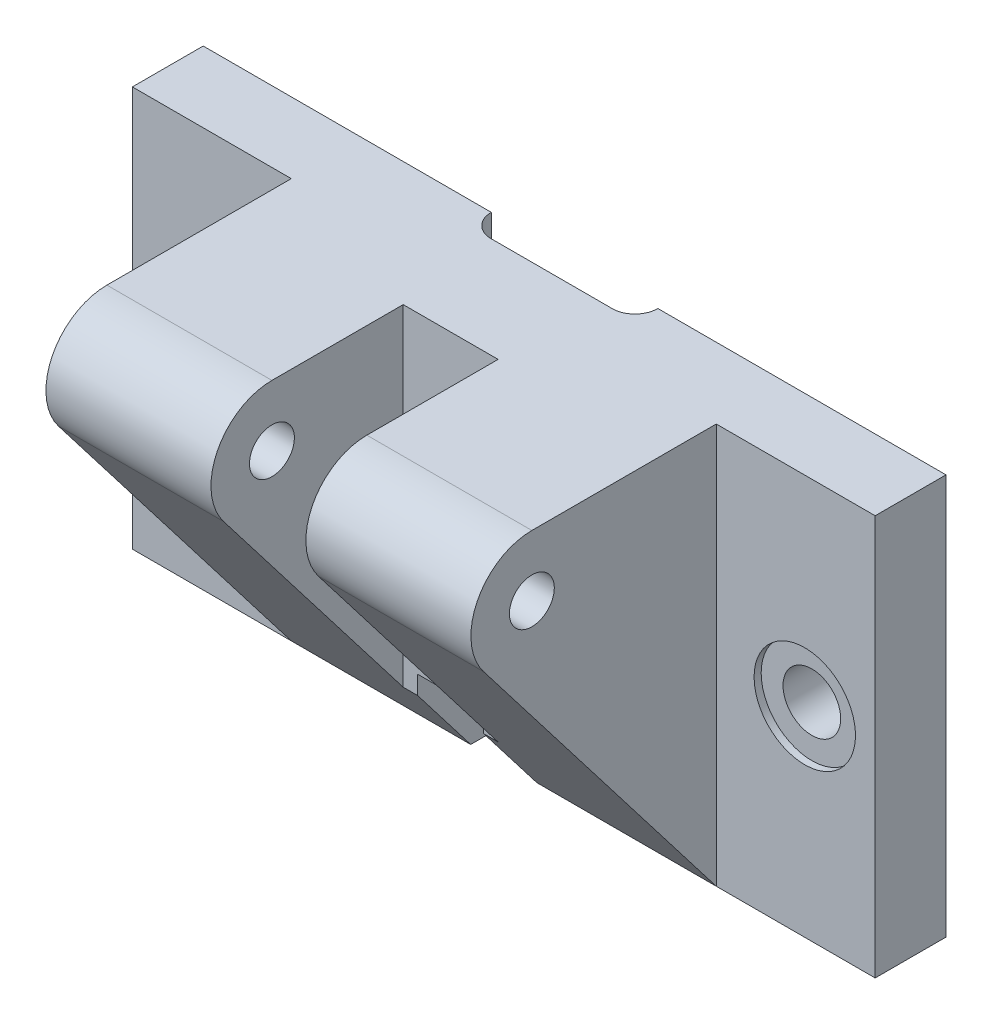
SolidWorks part; units mm, degrees
ref_plane "Płaszczyzna przednia" through (0, 0, 0) normal (0, 0, 1) x (1, 0, 0)
ref_plane "Płaszczyzna górna" through (0, 0, 0) normal (0, 1, 0) x (1, 0, 0)
ref_plane "Płaszczyzna prawa" through (0, 0, 0) normal (1, 0, 0) x (0, 0, -1)
sketch "Szkic1" plane through (0, 0, 0) normal (0, 0, 1) x (1, 0, 0)
  line L0 (0, 89.3165) -> (0, -100.7451) construction
  line L2 (0, 62.9812) -> (-104.8721, 62.9812)
  line L3 (0, 62.9812) -> (0, -50.062)
  line L4 (0, -50.062) -> (-104.8721, -50.062)
  line L5 (-104.8721, 62.9812) -> (-104.8721, -50.062)
  circle A0 centre (-84.9964, 6.4596) radius 8.1392
extrude "Dodanie-wyciągnięcie1" add sketch "Szkic1" along normal blind 20
ref_plane "Płaszczyzna1" through (0, 0, 20) normal (0, 0, 1) x (1, 0, 0)
sketch "Szkic2" plane through (0, 0, 20) normal (0, 0, 1) x (1, 0, 0)
  circle A0 centre (-84.9964, 6.4596) radius 14.3159
extrude "Wytnij-wyciągnięcie1" cut sketch "Szkic2" against normal blind 2 contours A0
mirror "Lustro2" about plane through (0, 62.9812, 20) normal (-1, 0, 0) of "Wytnij-wyciągnięcie1", "Dodanie-wyciągnięcie1"
ref_plane "Płaszczyzna2" through (0, 62.9812, 0) normal (0, 1, 0) x (1, 0, 0)
sketch "Szkic6" plane through (0, 62.9812, 0) normal (0, 1, 0) x (1, 0, 0)
  line L0 (-104.8721, -6.4678) -> (104.8721, -6.4678) construction
  line L1 (104.8721, -20) -> (104.8721, 0) construction
  line L2 (-104.8721, -20) -> (-104.8721, 0) construction
  line L3 (0, -6.4678) -> (0, -20) construction
  line L4 (-62.1737, -20) -> (62.1737, -20) construction
  line L5 (0, -20) -> (0, 0) construction
  line L6 (-23.533, 0) -> (23.533, 0)
  line L7 (104.8721, 0) -> (-104.8721, 0) construction
  line L8 (-16.4916, -6.4678) -> (16.4916, -6.4678)
  arc A0 (-23.533, 0) -> (-16.4916, -6.4678) centre (-17.0419, 0) ccw
  arc A1 (23.533, 0) -> (16.4916, -6.4678) centre (17.0419, 0) cw
  point P16 (0, 0)
extrude "Wytnij-wyciągnięcie2" cut sketch "Szkic6" against normal blind 140
sketch "Szkic9" plane through (0, 0, 0) normal (1, 0, 0) x (0, 0, -1)
  line L0 (-20, 62.9812) -> (-72.0689, 62.9812)
  line L1 (11, 62.9812) -> (-11, 62.9812) construction
  line L2 (-85.7036, 35.2757) -> (-20, -50.062)
  line L3 (-20, 62.1737) -> (-20, -62.1737) construction
  line L4 (-20, 62.9812) -> (-20, -50.062)
  arc A0 (-72.0689, 62.9812) -> (-85.7036, 35.2757) centre (-72.0689, 45.7734) ccw
  circle A1 centre (-72.0689, 45.7734) radius 6.341
extrude "Dodanie-wyciągnięcie2" add sketch "Szkic9" along normal blind 60
mirror "Lustro3" about plane through (0, 45.7734, 72.0689) normal (1, 0, 0) of "Dodanie-wyciągnięcie2"
ref_plane "Płaszczyzna3" through (0, 0, 35) normal (0, 0, 1) x (1, 0, 0)
sketch "Szkic12" plane through (0, 0, 35) normal (0, 0, 1) x (1, 0, 0)
  line L0 (0, 62.9812) -> (0, -50.062) construction
  line L1 (39.6379, 62.9812) -> (-39.6379, 62.9812) construction
  line L2 (60, -50.062) -> (-60, -50.062) construction
  line L3 (-13.4008, 62.9812) -> (13.4008, 62.9812)
  line L4 (13.4008, 62.9812) -> (13.4008, -50.062)
  line L5 (13.4008, -50.062) -> (-13.4008, -50.062)
  line L6 (-13.4008, -50.062) -> (-13.4008, 62.9812)
  point P10 (0, 0)
  point P11 (0, -50.062)
  point P12 (-13.4008, -50.062)
extrude "Wytnij-wyciągnięcie8" cut sketch "Szkic12" along normal blind 99
sketch "Szkic13" plane through (0, 0, 35) normal (0, 0, 1) x (1, 0, 0)
  line L0 (0, -25.3643) -> (0, -68.6154) construction
  line L1 (9.3383, -68.6154) -> (-9.3383, -68.6154)
  line L2 (9.3383, -68.6154) -> (9.3383, -25.3643)
  line L3 (9.3383, -25.3643) -> (-9.3383, -25.3643)
  line L4 (-9.3383, -68.6154) -> (-9.3383, -25.3643)
  line L5 (13.4008, -30.5795) -> (-13.4008, -30.5795) construction
  point P8 (0, -30.5795)
extrude "Wytnij-wyciągnięcie9" cut sketch "Szkic13" against normal blind 85
